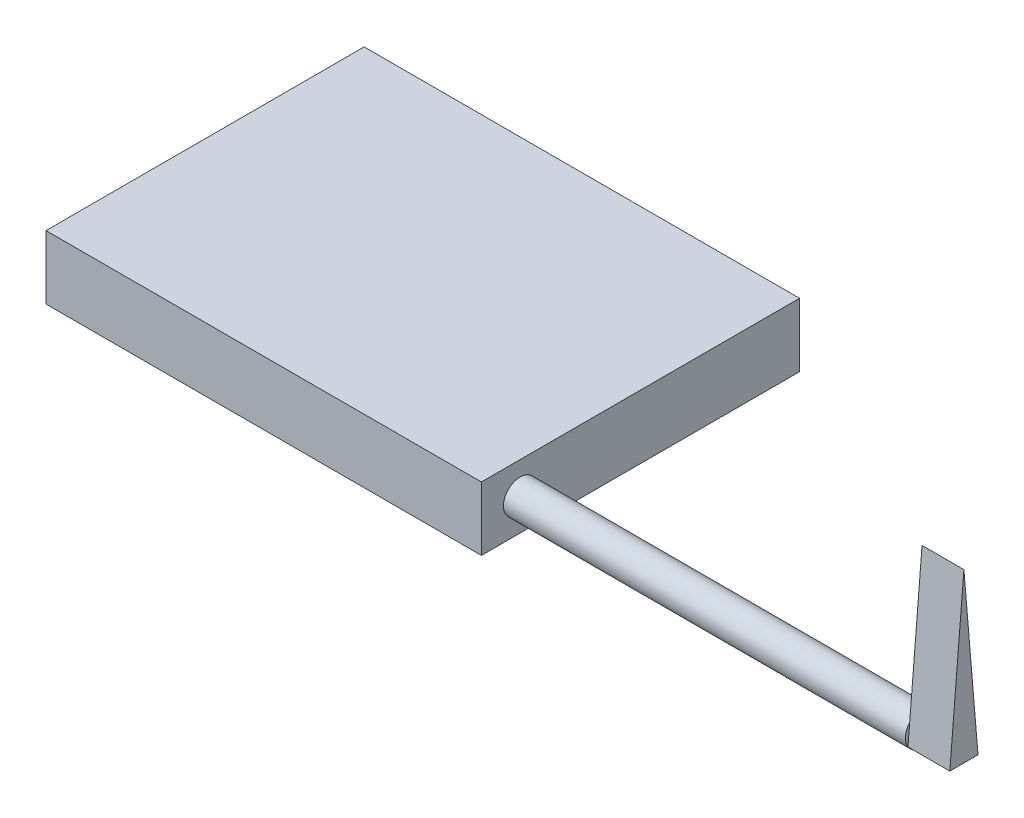
SolidWorks part; units mm, degrees
ref_plane "Front Plane" through (0, 0, 0) normal (0, 0, 1) x (1, 0, 0)
ref_plane "Top Plane" through (0, 0, 0) normal (0, 1, 0) x (1, 0, 0)
ref_plane "Right Plane" through (0, 0, 0) normal (1, 0, 0) x (0, 0, -1)
sketch "Sketch1" plane through (0, 0, 0) normal (0, 1, 0) x (1, 0, 0)
  line L1 (-40.7811, 19) -> (11.2189, 19)
  line L2 (-40.7811, 19) -> (-40.7811, -19)
  line L3 (-40.7811, -19) -> (11.2189, -19)
  line L4 (11.2189, 19) -> (11.2189, -19)
  dimension "D1" = 38
  dimension "D2" = 52
extrude "Boss-Extrude1" add sketch "Sketch1" along normal blind 7.6
sketch "Sketch2" plane through (11.2189, 0, 0) normal (1, 0, 0) x (0, 0, -1)
  line L0 (-19, 3.8) -> (19, 3.8) construction
  line L1 (-19, 7.6) -> (-19, 0) construction
  line L2 (19, 7.6) -> (19, 0) construction
  circle A0 centre (-14.3682, 3.8) radius 2
extrude "Boss-Extrude2" add sketch "Sketch2" along normal blind 48
sketch "Sketch3" plane through (59.2189, 0, 0) normal (1, 0, 0) x (0, 0, -1)
  line L0 (-16.0506, 2.7185) -> (-12.6859, 2.7185)
  line L1 (-12.6859, 2.7185) -> (-14.3682, 22.7185)
  line L2 (-14.3682, 22.7185) -> (-16.0506, 2.7185)
  circle A0 centre (-14.3682, 3.8) radius 2 construction
  dimension "D1" = 20
extrude "Boss-Extrude3" add sketch "Sketch3" along normal blind 5
